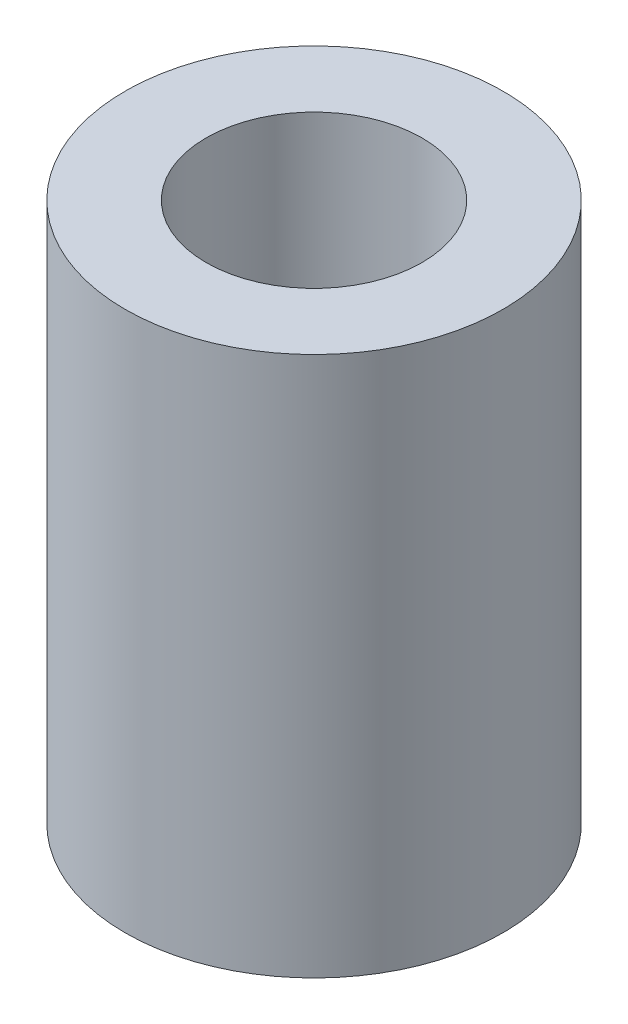
SolidWorks part; units mm, degrees
ref_plane "Спереди" through (0, 0, 0) normal (0, 0, 1) x (1, 0, 0)
ref_plane "Сверху" through (0, 0, 0) normal (0, 1, 0) x (1, 0, 0)
ref_plane "Справа" through (0, 0, 0) normal (1, 0, 0) x (0, 0, -1)
sketch "Эскиз1" plane through (0, 0, 0) normal (0, 1, 0) x (1, 0, 0)
  circle A0 centre (0, 0) radius 2
  circle A1 centre (0, 0) radius 3.5
  dimension "D1" = 4
  dimension "D2" = 7
extrude "Бобышка-Вытянуть1" add sketch "Эскиз1" along normal blind 10
